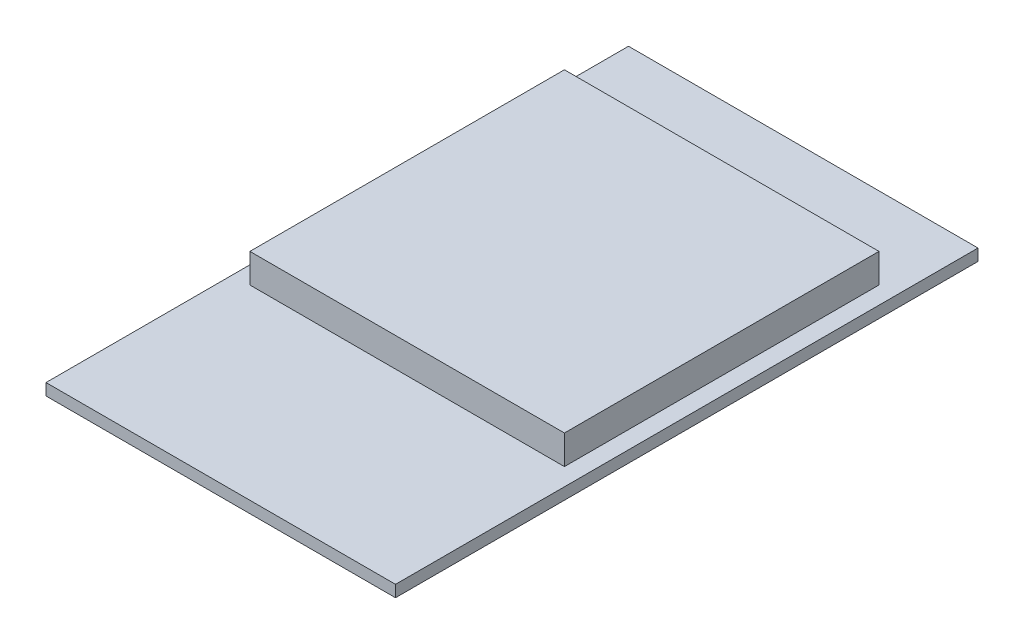
SolidWorks part; units mm, degrees
ref_plane "Front Plane" through (0, 0, 0) normal (0, 0, 1) x (1, 0, 0)
ref_plane "Top Plane" through (0, 0, 0) normal (0, 1, 0) x (1, 0, 0)
ref_plane "Right Plane" through (0, 0, 0) normal (1, 0, 0) x (0, 0, -1)
sketch "Sketch1" plane through (0, 0, 0) normal (0, 1, 0) x (1, 0, 0)
  line L1 (0, 0) -> (30, 0)
  line L2 (0, 0) -> (0, 50)
  line L3 (0, 50) -> (30, 50)
  line L4 (30, 0) -> (30, 50)
  dimension "D1" = 30
  dimension "D2" = 50
extrude "Boss-Extrude1" add sketch "Sketch1" along normal blind 1
sketch "Sketch2" plane through (0, 1, 0) normal (0, 1, 0) x (1, 0, 0)
  line L0 (30, 50) -> (0, 50) construction
  line L1 (1.5, 16) -> (28.5, 16)
  line L2 (1.5, 16) -> (1.5, 43)
  line L3 (1.5, 43) -> (28.5, 43)
  line L4 (28.5, 16) -> (28.5, 43)
  line L5 (15, 50) -> (15, 0) construction
  line L6 (0, 0) -> (30, 0) construction
  line L7 (15, 43) -> (15, 16) construction
  dimension "D1" = 27
  dimension "D2" = 7
extrude "Boss-Extrude2" add sketch "Sketch2" along normal blind 2.5
sketch "Sketch3" plane through (0, 3.5, 0) normal (0, 1, 0) x (1, 0, 0)
  text T0 "Mini PCIe"
